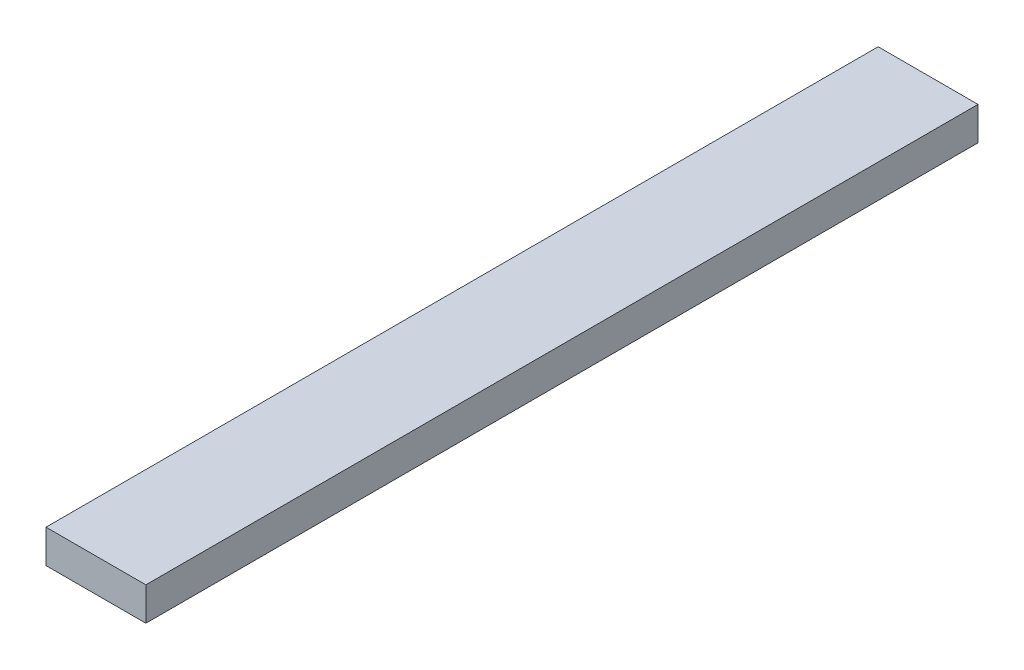
SolidWorks part; units mm, degrees
ref_plane "Front Plane" through (0, 0, 0) normal (0, 0, 1) x (1, 0, 0)
ref_plane "Top Plane" through (0, 0, 0) normal (0, 1, 0) x (1, 0, 0)
ref_plane "Right Plane" through (0, 0, 0) normal (1, 0, 0) x (0, 0, -1)
sketch "Sketch2" plane through (0, 0, 0) normal (0, 1, 0) x (1, 0, 0)
  line L1 (-30, 250) -> (30, 250)
  line L2 (-30, 250) -> (-30, -250)
  line L3 (-30, -250) -> (30, -250)
  line L4 (30, 250) -> (30, -250)
  line L5 (-30, 250) -> (30, -250) construction
  line L6 (-30, -250) -> (30, 250) construction
  point P0 (0, 0)
  dimension "D1" = 500
  dimension "D2" = 60
extrude "Boss-Extrude1" add sketch "Sketch2" along normal mid plane 20
